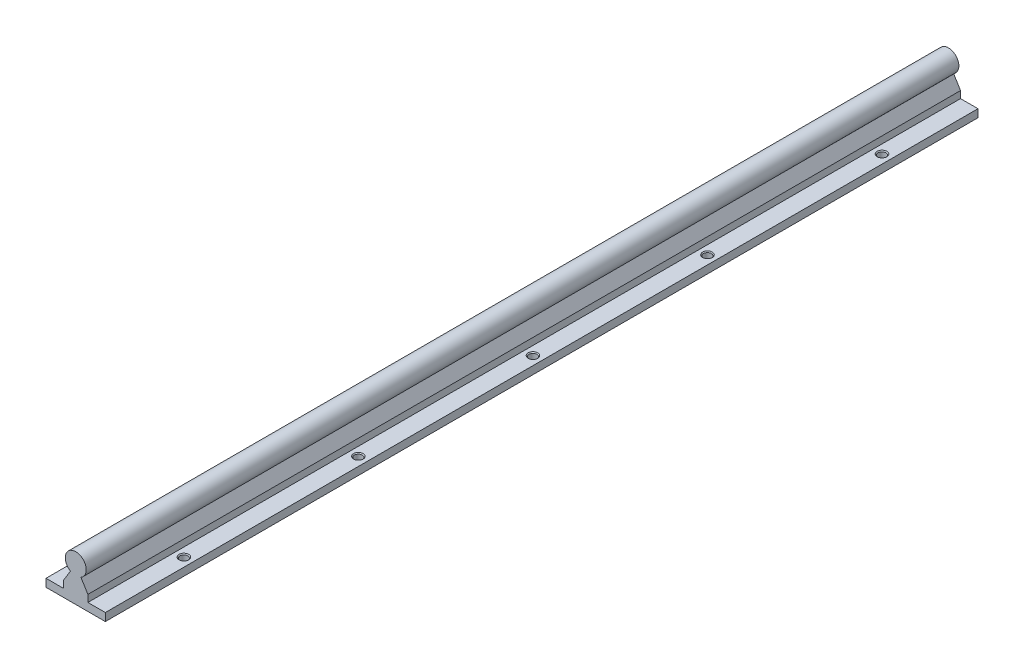
SolidWorks part; units mm, degrees
ref_plane "Plan de face" through (0, 0, 0) normal (0, 0, 1) x (1, 0, 0)
ref_plane "Plan de dessus" through (0, 0, 0) normal (0, 1, 0) x (1, 0, 0)
ref_plane "Plan de droite" through (0, 0, 0) normal (1, 0, 0) x (0, 0, -1)
sketch "Esquisse1" plane through (0, 0, 0) normal (0, 0, 1) x (1, 0, 0)
  line L0 (-38.8855, -19.8216) -> (-4.8855, -19.8216)
  line L1 (-4.8855, -19.8216) -> (-4.8855, -15.3216)
  line L2 (-4.8855, -15.3216) -> (-14.8855, -15.3216)
  line L3 (-14.8855, -15.3216) -> (-14.8855, -11.3216)
  line L4 (-14.8855, -11.3216) -> (-18.8855, -4.8216)
  line L7 (-24.8855, -4.769) -> (-28.8855, -11.3216)
  line L8 (-28.8855, -11.3216) -> (-28.8855, -15.3216)
  line L9 (-28.8855, -15.3216) -> (-38.8855, -15.3216)
  line L10 (-38.8855, -15.3216) -> (-38.8855, -19.8216)
  arc A0 (-18.8855, -4.8216) -> (-24.8855, -4.769) centre (-21.8399, 0.4006) ccw
  dimension "D11" = 12
  dimension "D1" = 4.5
  dimension "D2" = 4
  dimension "D3" = 34
  dimension "D4" = 14
  dimension "D5" = 10
  dimension "D6" = 6
  dimension "D9" = 15
  dimension "D10" = 4
extrude "Extrusion1" add sketch "Esquisse1" along normal blind 500
hole_wizard "Fraisage pour vis à tête fraisée M41" positions "Esquisse3D1" profile "Esquisse2" countersink size "M4" standard "Ansi Métrique" end condition through all
sketch3d "Esquisse3D1"
  line L0 (-28.8855, -15.3216, 0) -> (-38.8855, -15.3216, 0) construction
  line L1 (-4.8855, -15.3216, 0) -> (-14.8855, -15.3216, 0) construction
  line L2 (-38.8855, -15.3216, 500) -> (-38.8855, -15.3216, 0) construction
  line L3 (-4.8855, -15.3216, 500) -> (-4.8855, -15.3216, 0) construction
  point P0 (-33.8855, -15.3216, 50)
  point P2 (-33.8855, -15.3216, 150)
  point P4 (-33.8855, -15.3216, 250)
  point P10 (-9.8855, -15.3216, 250)
  point P12 (-9.8855, -15.3216, 150)
  point P14 (-9.8855, -15.3216, 50)
  point P38 (-9.8855, -15.3216, 350)
  point P40 (-9.8855, -15.3216, 450)
  point P42 (-33.8855, -15.3216, 350)
  point P44 (-33.8855, -15.3216, 450)
  dimension "D1" = 50
  dimension "D2" = 150
  dimension "D3" = 250
  dimension "D4" = 50
  dimension "D5" = 150
  dimension "D6" = 250
  dimension "D7" = 5
  dimension "D8" = 5
  dimension "D9" = 350
  dimension "D11" = 350
  dimension "D10" = 450
  dimension "D12" = 450
sketch "Esquisse2" plane through (-33.8855, -15.3216, 50) normal (1, 0, 0) x (0, 0, 1)
  line L0 (0, 0) -> (0, 4.5)
  line L1 (0, 4.5) -> (2.25, 4.5)
  line L2 (2.25, 4.5) -> (2.25, 0.5)
  line L3 (2.25, 0.5) -> (2.75, 0)
  line L5 (2.75, 0) -> (0, 0)
  line L6 (-2.25, 0.5) -> (-2.75, 0) construction
  line L11 (0, -6.35) -> (0, 107.95) construction
  dimension "Diamètre du perçage jusqu'au prochain" = 4.5
  dimension "Profondeur du perçage jusqu'au prochain" = 4.5
  dimension "Diamètre du fraisage entrant" = 5.5
  dimension "Angle du fraisage entrant" = 90
